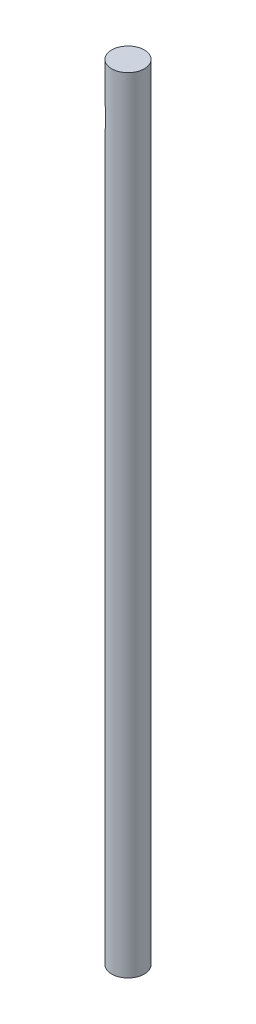
SolidWorks part; units mm, degrees
material "Cast Carbon Steel"
ref_plane "Front Plane" through (0, 0, 0) normal (0, 0, 1) x (1, 0, 0)
ref_plane "Top Plane" through (0, 0, 0) normal (0, 1, 0) x (1, 0, 0)
ref_plane "Right Plane" through (0, 0, 0) normal (1, 0, 0) x (0, 0, -1)
sketch "Sketch1" plane through (0, 0, 0) normal (0, 1, 0) x (1, 0, 0)
  circle A0 centre (0, 0) radius 12.7
  dimension "D1" = 25.4
extrude "Boss-Extrude1" add sketch "Sketch1" along normal blind 609.6
ref_plane "Plane1" through (0, 0, 0) normal (0, -1, 0) x (-1, 0, 0)
ref_plane "Plane2" through (-12.7, 0, 0) normal (-1, 0, 0) x (0, 0, 1)
sketch "Sketch3" plane through (-12.7, 0, 0) normal (-1, 0, 0) x (0, 0, 1)
  line L0 (-12.7, 0) -> (12.7, 0) construction
  circle A0 centre (0, 571.754) radius 12.7
  dimension "D1" = 25.4
  dimension "D2" = 571.754
extrude "Cut-Extrude1" cut sketch "Sketch3" against normal blind 6.35
